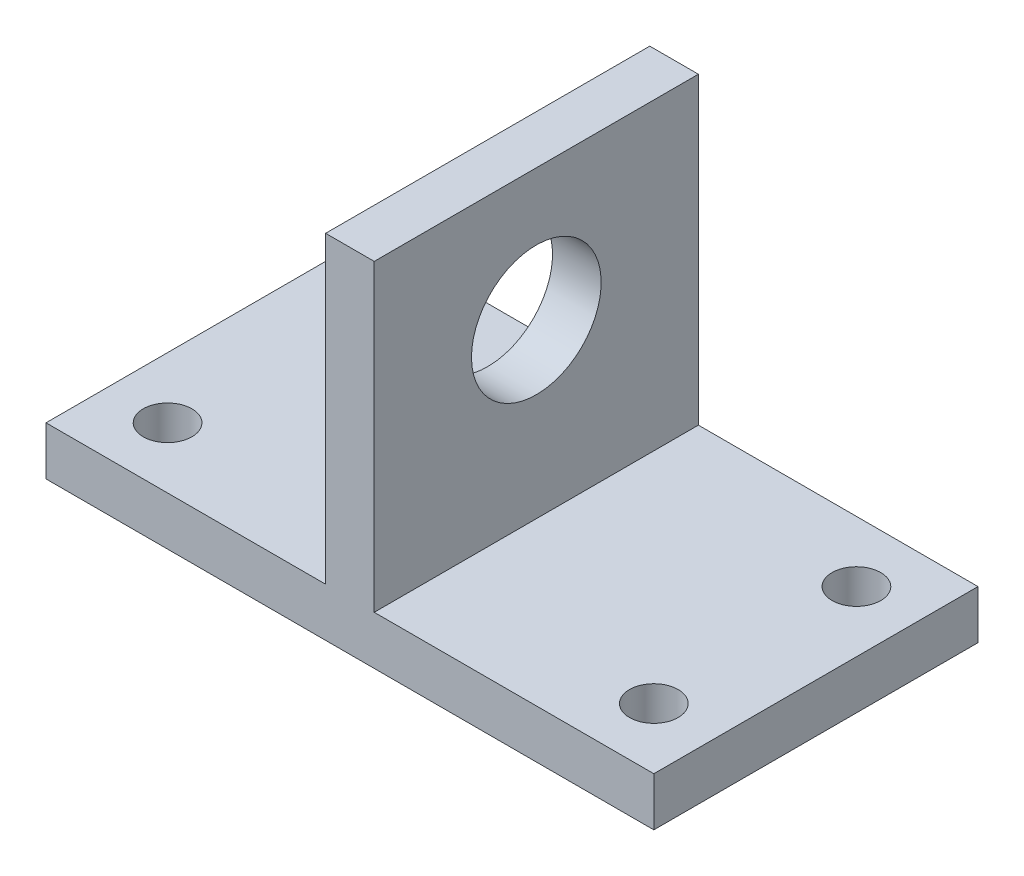
SolidWorks part; units mm, degrees
material "AISI 1020"
ref_plane "Plano frontal" through (0, 0, 0) normal (0, 0, 1) x (1, 0, 0)
ref_plane "Plano superior" through (0, 0, 0) normal (0, 1, 0) x (1, 0, 0)
ref_plane "Plano direito" through (0, 0, 0) normal (1, 0, 0) x (0, 0, -1)
sketch "Esboço1" plane through (0, 0, 0) normal (0, 1, 0) x (1, 0, 0)
  line L1 (-75, 40) -> (75, 40)
  line L2 (-75, 40) -> (-75, -40)
  line L3 (-75, -40) -> (75, -40)
  line L4 (75, 40) -> (75, -40)
  line L5 (-75, 40) -> (75, -40) construction
  line L6 (-75, -40) -> (75, 40) construction
  circle A0 centre (-60, 25) radius 6
  circle A1 centre (-60, -25) radius 6
  circle A2 centre (60, 25) radius 6
  circle A3 centre (60, -25) radius 6
  point P0 (0, 0)
  dimension "D3" = 12
  dimension "D4" = 12
  dimension "D5" = 12
  dimension "D6" = 12
  dimension "D9" = 120
  dimension "D10" = 15
  dimension "D11" = 15
  dimension "D12" = 15
  dimension "D13" = 15
  dimension "D14" = 120
  dimension "D1" = 150
  dimension "D2" = 80
  dimension "D7" = 50
  dimension "D8" = 50
extrude "Ressalto-extrusão1" add sketch "Esboço1" along normal blind 12
sketch "Esboço2" plane through (0, 12, 0) normal (0, 1, 0) x (1, 0, 0)
  line L0 (-75, -40) -> (75, -40) construction
  line L1 (-6, 40) -> (6, 40)
  line L2 (-6, 40) -> (-6, -40)
  line L3 (-6, -40) -> (6, -40)
  line L4 (6, 40) -> (6, -40)
  line L5 (-6, 40) -> (6, -40) construction
  line L6 (-6, -40) -> (6, 40) construction
  point P0 (0, 0)
  dimension "D1" = 12
extrude "Ressalto-extrusão2" add sketch "Esboço2" along normal blind 75
sketch "Esboço3" plane through (-6, 0, 0) normal (-1, 0, 0) x (0, 0, 1)
  line L0 (-40, 87) -> (-40, 12) construction
  line L3 (-40, 87) -> (40, 87) construction
  circle A0 centre (0, 54.5) radius 16
  dimension "D1" = 32
  dimension "D2" = 40
  dimension "D3" = 32.5
extrude "Corte-extrusão1" cut sketch "Esboço3" against normal through all
